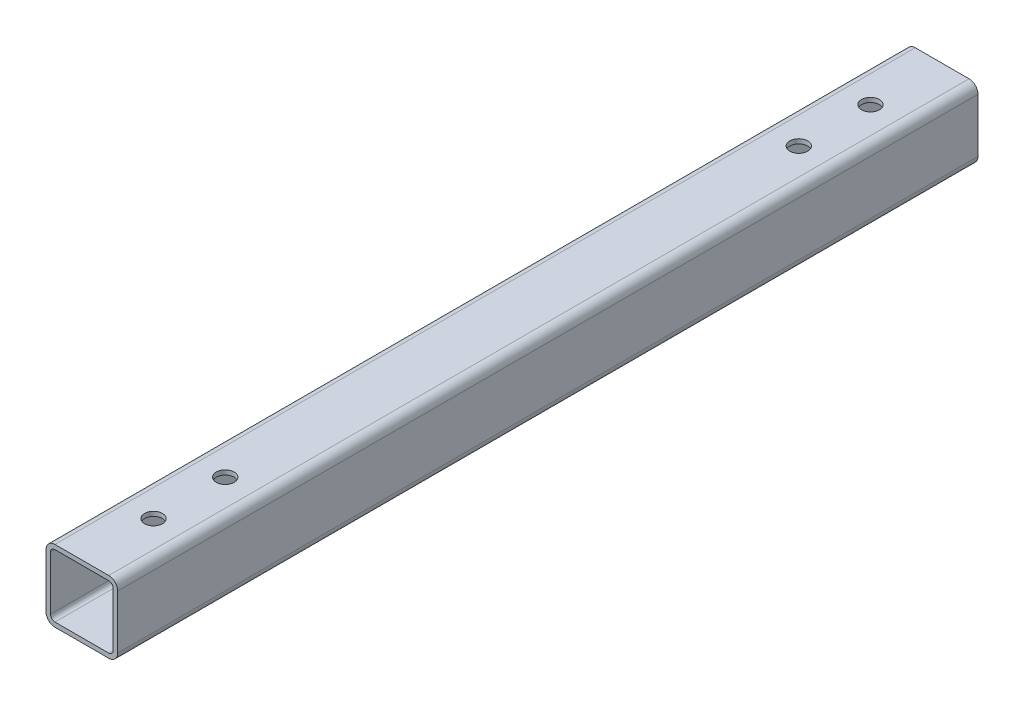
SolidWorks part; units mm, degrees
ref_plane "Front" through (0, 0, 0) normal (0, 0, 1) x (1, 0, 0)
ref_plane "Top" through (0, 0, 0) normal (0, 1, 0) x (1, 0, 0)
ref_plane "Right" through (0, 0, 0) normal (1, 0, 0) x (0, 0, -1)
sketch "Sketch1" plane through (0, 0, 0) normal (0, 0, 1) x (1, 0, 0)
  line L0 (-12.7, 12.7) -> (12.7, 12.7)
  line L1 (-12.7, 12.7) -> (-12.7, -12.7)
  line L2 (12.7, -12.7) -> (-12.7, -12.7)
  line L3 (12.7, -12.7) -> (12.7, 12.7)
  line L4 (-12.7, -12.7) -> (12.7, 12.7) construction
  dimension "square" = 25.4
extrude "Base-Extrude" add sketch "Sketch1" along normal mid plane 304.8
fillet "Fillet1" radius 3.175 4 edges at (-12.7, 12.7, 0) (12.7, 12.7, 0) (12.7, -12.7, 0) (-12.7, -12.7, 0)
shell "Shell1" thickness 1.5875
sketch "Sketch5" plane through (0, -12.7, 0) normal (0, -1, 0) x (1, 0, 0)
  line L0 (0, -152.4) -> (0, 152.4) construction
  line L1 (9.525, -152.4) -> (-9.525, -152.4) construction
  line L2 (9.525, 152.4) -> (-9.525, 152.4) construction
  circle A2 centre (0, 127) radius 3.175
  circle A3 centre (0, 101.6) radius 3.175
  circle A6 centre (0, -127) radius 3.175
  circle A7 centre (0, -101.6) radius 3.175
  dimension "D3" = 6.35
  dimension "D1" = 25.4
  dimension "D2" = 50.8
  dimension "D4" = 50.8
  dimension "D5" = 25.4
extrude "Cut-Extrude2" cut sketch "Sketch5" against normal through all
